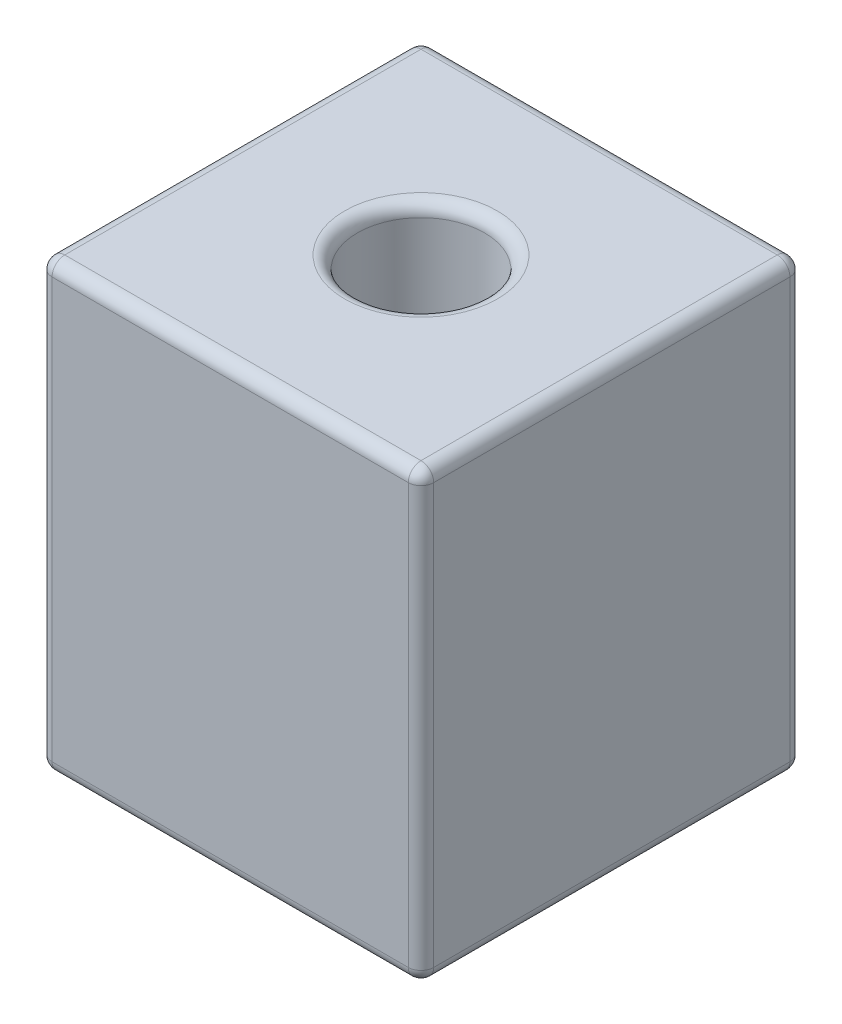
SolidWorks part; units mm, degrees
ref_plane "Front Plane" through (0, 0, 0) normal (0, 0, 1) x (1, 0, 0)
ref_plane "Top Plane" through (0, 0, 0) normal (0, 1, 0) x (1, 0, 0)
ref_plane "Right Plane" through (0, 0, 0) normal (1, 0, 0) x (0, 0, -1)
sketch "Sketch1" plane through (0, 0, 0) normal (0, 0, 1) x (1, 0, 0)
  line L1 (-15, -17.5) -> (15, -17.5)
  line L2 (-15, -17.5) -> (-15, 17.5)
  line L3 (-15, 17.5) -> (15, 17.5)
  line L4 (15, -17.5) -> (15, 17.5)
  line L5 (-15, -17.5) -> (15, 17.5) construction
  line L6 (-15, 17.5) -> (15, -17.5) construction
  point P0 (0, 0)
  dimension "D1" = 30
  dimension "D2" = 35
extrude "Boss-Extrude1" add sketch "Sketch1" along normal blind 30
sketch "Sketch2" plane through (0, 17.5, 0) normal (0, 1, 0) x (1, 0, 0)
  line L0 (-15, -15) -> (15, -15) construction
  line L1 (-15, -30) -> (-15, 0) construction
  line L2 (15, -30) -> (15, 0) construction
  line L3 (0, 0) -> (0, -30) construction
  line L4 (15, -30) -> (-15, -30) construction
  circle A0 centre (0, -15) radius 5
  dimension "D1" = 10
extrude "Cut-Extrude1" cut sketch "Sketch2" against normal blind 30
fillet "Fillet2" radius 1 14 edges at (0, -17.5, 30) (0, 17.5, 30) (15, -17.5, 15) (15, 0, 30) (15, 17.5, 15) (0, 17.5, 0) (0, -17.5, 0) (15, 0, 0) (-15, 17.5, 15) (-15, 0, 30) (-15, -17.5, 15) (-15, 0, 0) (0, 17.5, 20) (0, -12.5, 20)
